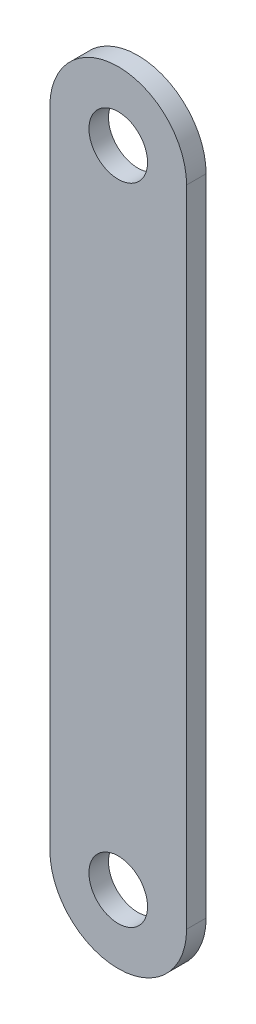
SolidWorks part; units mm, degrees
ref_plane "Front Plane" through (0, 0, 0) normal (0, 0, 1) x (1, 0, 0)
ref_plane "Top Plane" through (0, 0, 0) normal (0, 1, 0) x (1, 0, 0)
ref_plane "Right Plane" through (0, 0, 0) normal (1, 0, 0) x (0, 0, -1)
sketch "Sketch1" plane through (0, 0, 0) normal (0, 0, 1) x (1, 0, 0)
  line L0 (0, 0) -> (0, 33) construction
  line L4 (3.5, 0) -> (3.5, 33)
  line L5 (-3.5, 0) -> (-3.5, 33)
  circle A0 centre (0, 33) radius 1.5
  circle A1 centre (0, 0) radius 1.5
  circle A2 centre (0, 0) radius 3.5
  circle A3 centre (0, 33) radius 3.5
  dimension "D1" = 3
  dimension "D2" = 3
  dimension "D3" = 33
  dimension "D6" = 2
sketch "Sketch2" plane through (0, 0, 0) normal (0, 0, 1) x (1, 0, 0)
  line L0 (-3.5, 0) -> (-3.5, 33) construction
  line L1 (3.5, 0) -> (3.5, 33) construction
  line L2 (-3.5, 0) -> (-3.5, 33)
  line L3 (3.5, 0) -> (3.5, 33)
  circle A0 centre (0, 33) radius 3.5 construction
  circle A1 centre (0, 33) radius 1.5 construction
  circle A2 centre (0, 0) radius 3.5 construction
  circle A3 centre (0, 0) radius 1.5 construction
  arc A4 (3.5, 33) -> (-3.5, 33) centre (0, 33) ccw
  circle A5 centre (0, 33) radius 1.5
  arc A6 (-3.5, 0) -> (3.5, 0) centre (0, 0) ccw
  circle A7 centre (0, 0) radius 1.5
extrude "Boss-Extrude1" add sketch "Sketch2" along normal blind 1
